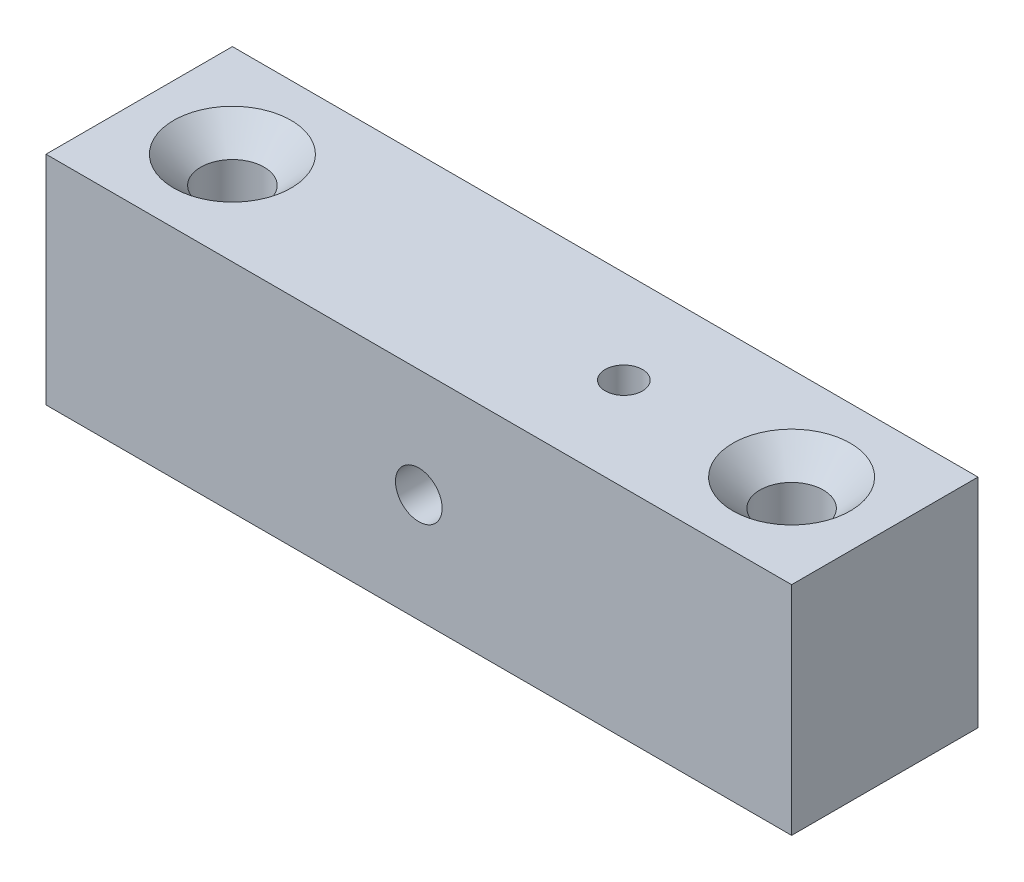
SolidWorks part; units mm, degrees
material "Copper"
ref_plane "Front Plane" through (0, 0, 0) normal (0, 0, 1) x (1, 0, 0)
ref_plane "Top Plane" through (0, 0, 0) normal (0, 1, 0) x (1, 0, 0)
ref_plane "Right Plane" through (0, 0, 0) normal (1, 0, 0) x (0, 0, -1)
sketch "Sketch1" plane through (0, 0, 0) normal (0, 1, 0) x (1, 0, 0)
  line L0 (0, 5) -> (40, 5) construction
  line L1 (0, 0) -> (40, 0)
  line L2 (0, 0) -> (0, 10)
  line L3 (0, 10) -> (40, 10)
  line L4 (40, 0) -> (40, 10)
  line L5 (5, 5) -> (5, 10) construction
  line L6 (35, 10) -> (35, 5) construction
  dimension "D1" = 5
  dimension "D2" = 5
  dimension "D3" = 5
  dimension "D4" = 5
  dimension "D5" = 40
extrude "Boss-Extrude1" add sketch "Sketch1" along normal blind 11.65
sketch "Sketch2" plane through (0, 11.65, 0) normal (0, 1, 0) x (1, 0, 0)
  point P0 (35, 5)
  point P2 (5, 5)
hole_wizard "CSK for M3 Flat Head Machine Screw1" positions "3DSketch1" profile "Sketch3" countersink size "M3" standard "ANSI Metric" end condition through all
sketch3d "3DSketch1"
  point P0 (5, 11.65, -5)
  point P3 (35, 11.65, -5)
sketch "Sketch3" plane through (5, 11.65, -5) normal (1, 0, 0) x (0, 0, 1)
  line L0 (0, 0) -> (0, 11.65)
  line L1 (0, 11.65) -> (1.7, 11.65)
  line L2 (1.7, 11.65) -> (1.7, 1.45)
  line L3 (1.7, 1.45) -> (3.15, 0)
  line L5 (3.15, 0) -> (0, 0)
  line L6 (-1.7, 1.45) -> (-3.15, 0) construction
  line L11 (0, -6.35) -> (0, 107.95) construction
  dimension "Thru Hole Dia." = 3.4
  dimension "Thru Hole Depth" = 11.65
  dimension "Near C'Sink Dia." = 6.3
  dimension "Near C'Sink Angle" = 90
ref_plane "Plane1" through (20, 0, 0) normal (-1, 0, 0) x (0, 0, 1)
sketch "Sketch4" plane through (0, 0, -10) normal (0, 0, -1) x (-1, 0, 0)
  line L0 (-40, 5.825) -> (0, 5.825) construction
  line L1 (-40, 11.65) -> (-40, 0) construction
  line L2 (0, 11.65) -> (0, 0) construction
hole_wizard "M3x0.5 Tapped Hole1" positions "3DSketch2" profile "Sketch5" tap size "M3x0.5" standard "ANSI Metric" end condition through all
sketch3d "3DSketch2"
  line L0 (40, 5.825, -10) -> (0, 5.825, -10) construction
  point P0 (20, 5.825, -10)
  point P4 (20, 5.825, -10)
cosmetic thread "Hole Thread1" parameters "D2"=3
cosmetic thread "Hole Thread2" parameters "D2"=3
sketch "Sketch5" plane through (20, 5.825, -10) normal (1, 0, 0) x (0, 1, 0)
  line L0 (0, 0) -> (0, 10)
  line L1 (0, 10) -> (1.25, 10)
  line L2 (1.25, 10) -> (1.25, 0)
  line L5 (1.25, 0) -> (0, 0)
  line L11 (0, -6.35) -> (0, 107.95) construction
  dimension "Thru Tap Drill Dia." = 2.5
  dimension "Thru Tap Drill Depth" = 10
sketch "Sketch6" plane through (0, 11.65, 0) normal (0, 1, 0) x (1, 0, 0)
  line L0 (40, 5) -> (26, 5) construction
  line L1 (40, 0) -> (40, 10) construction
  dimension "D1" = 14
hole_wizard "Ø2.0mm Dowel Hole1" positions "3DSketch3" profile "Sketch7" hole size "Ø2.0" standard "ANSI Metric" end condition through all
sketch3d "3DSketch3"
  point P0 (26, 11.65, -5)
sketch "Sketch7" plane through (26, 11.65, -5) normal (1, 0, 0) x (0, 0, 1)
  line L0 (0, 0) -> (0, 11.65)
  line L1 (0, 11.65) -> (1, 11.65)
  line L2 (1, 11.65) -> (1, 0)
  line L5 (1, 0) -> (0, 0)
  line L11 (0, -6.35) -> (0, 107.95) construction
  dimension "Thru Hole Dia." = 2
  dimension "Thru Hole Depth" = 11.65
equation "\"D2@Sketch1\"=\"D1@Sketch1\""
equation "\"D3@Sketch1\"=\"D1@Sketch1\""
